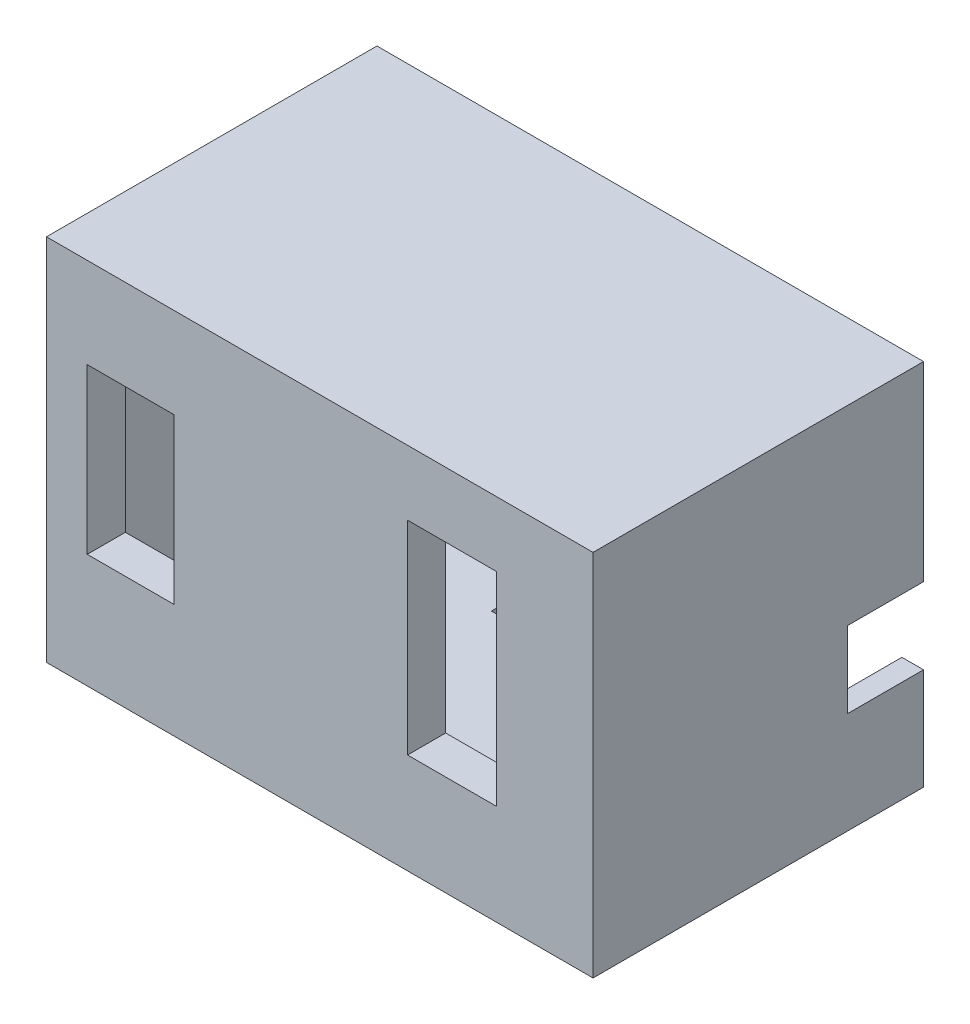
SolidWorks part; units mm, degrees
ref_plane "Front Plane" through (0, 0, 0) normal (0, 0, 1) x (1, 0, 0)
ref_plane "Top Plane" through (0, 0, 0) normal (0, 1, 0) x (1, 0, 0)
ref_plane "Right Plane" through (0, 0, 0) normal (1, 0, 0) x (0, 0, -1)
sketch "Sketch1" plane through (0, 0, 0) normal (0, 0, 1) x (1, 0, 0)
  line L1 (-107.5, 72.5) -> (107.5, 72.5)
  line L2 (-107.5, 72.5) -> (-107.5, -72.5)
  line L3 (-107.5, -72.5) -> (107.5, -72.5)
  line L4 (107.5, 72.5) -> (107.5, -72.5)
  line L5 (-107.5, 72.5) -> (107.5, -72.5) construction
  line L6 (-107.5, -72.5) -> (107.5, 72.5) construction
  point P0 (0, 0)
  dimension "D1" = 215
  dimension "D2" = 145
extrude "Boss-Extrude1" add sketch "Sketch1" along normal blind 130
sketch "Sketch3" plane through (-107.5, 0, 0) normal (-1, 0, 0) x (0, 0, 1)
  line L0 (0, -2.5) -> (30, -2.5)
  line L1 (0, 72.5) -> (0, -72.5) construction
  line L2 (30, -2.5) -> (30, -32.5)
  line L3 (30, -32.5) -> (0, -32.5)
  line L4 (0, -2.5) -> (0, -32.5)
  dimension "D1" = 75
  dimension "D2" = 30
  dimension "D3" = 30
extrude "Cut-Extrude1" cut sketch "Sketch3" against normal through all
sketch "Sketch4" plane through (0, 0, 0) normal (0, 0, -1) x (-1, 0, 0)
  line L1 (-99, 62.5) -> (99, 62.5)
  line L2 (-99, 62.5) -> (-99, -62.5)
  line L3 (-99, -62.5) -> (99, -62.5)
  line L4 (99, 62.5) -> (99, -62.5)
  line L5 (-99, 62.5) -> (99, -62.5) construction
  line L6 (-99, -62.5) -> (99, 62.5) construction
  point P0 (0, 0)
  dimension "D1" = 198
  dimension "D2" = 125
extrude "Cut-Extrude2" cut sketch "Sketch4" against normal blind 115
sketch "Sketch5" plane through (0, 0, 130) normal (0, 0, 1) x (1, 0, 0)
  line L0 (-91.4622, 36.9815) -> (-91.4622, -27.6487)
  line L1 (-91.4622, -27.6487) -> (-57.3972, -27.6487)
  line L2 (-57.3972, -27.6487) -> (-57.3972, 36.9815)
  line L3 (-57.3972, 36.9815) -> (-91.4622, 36.9815)
extrude "Cut-Extrude3" cut sketch "Sketch5" against normal blind 115
sketch "Sketch6" plane through (0, 0, 130) normal (0, 0, 1) x (1, 0, 0)
  line L0 (34.5317, 46.9849) -> (34.5317, -33.0151)
  line L1 (34.5317, -33.0151) -> (69.5317, -33.0151)
  line L2 (34.5317, 46.9849) -> (69.5317, 46.9849)
  line L3 (69.5317, 46.9849) -> (69.5317, -33.0151)
  dimension "D1" = 80
  dimension "D2" = 35
extrude "Cut-Extrude4" cut sketch "Sketch6" against normal blind 115
sketch "Sketch7" plane through (0, -72.5, 0) normal (0, -1, 0) x (1, 0, 0)
  line L0 (-27.5, 0) -> (-27.5, 35)
  line L1 (-107.5, 0) -> (107.5, 0) construction
  line L2 (-27.5, 35) -> (32.5, 35)
  line L3 (32.5, 35) -> (32.5, 0)
  line L4 (32.5, 0) -> (-27.5, 0)
  dimension "D1" = 80
  dimension "D2" = 60
  dimension "D3" = 35
extrude "Cut-Extrude5" cut sketch "Sketch7" against normal blind 115
